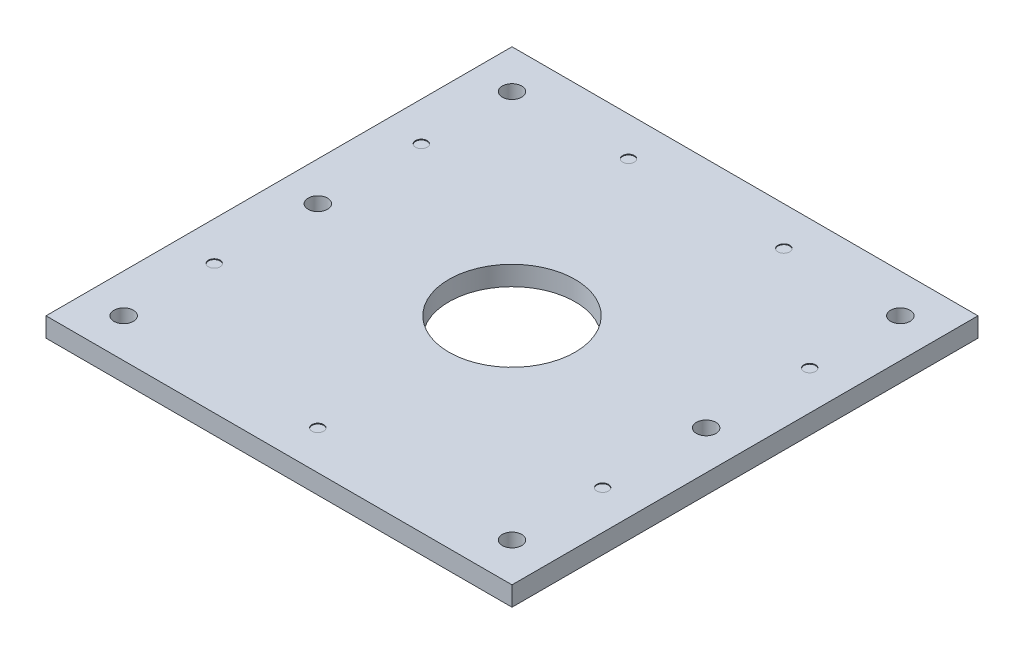
SolidWorks part; units mm, degrees
ref_plane "Front Plane" through (0, 0, 0) normal (0, 0, 1) x (1, 0, 0)
ref_plane "Top Plane" through (0, 0, 0) normal (0, 1, 0) x (1, 0, 0)
ref_plane "Right Plane" through (0, 0, 0) normal (1, 0, 0) x (0, 0, -1)
sketch "Sketch1" plane through (0, 0, 0) normal (0, 0, 1) x (1, 0, 0)
  line L7 (-76.2, -3.175) -> (76.2, -3.175)
  line L8 (-76.2, -3.175) -> (-76.2, 3.175)
  line L9 (-76.2, 3.175) -> (76.2, 3.175)
  line L10 (76.2, -3.175) -> (76.2, 3.175)
  line L11 (-76.2, -3.175) -> (76.2, 3.175) construction
  line L12 (-76.2, 3.175) -> (76.2, -3.175) construction
  point P4 (0, 0)
  point P14 (0, 0)
  dimension "Thickness" = 6.35
  dimension "Width" = 152.4
sketch "Sketch2" plane through (0, 0, 0) normal (0, 1, 0) x (0, 0, -1)
  line L0 (76.2, 76.2) -> (-76.2, 76.2) construction
  point P4 (0, 76.2)
  dimension "Length" = 152.4
sketch "Sketch3" plane through (0, 0, 0) normal (0, 0, 1) x (1, 0, 0)
  line L6 (-76.2, 3.175) -> (76.2, 3.175)
  line L7 (76.2, 3.175) -> (76.2, -3.175)
  line L8 (76.2, -3.175) -> (-76.2, -3.175)
  line L9 (-76.2, -3.175) -> (-76.2, 3.175)
extrude "Boss-Extrude1" add sketch "Sketch3" along normal mid plane 152.4
sketch "Sketch4" plane through (0, 3.175, 0) normal (0, 1, 0) x (1, 0, 0)
  line L0 (-76.2, -76.2) -> (-76.2, 76.2) construction
  line L1 (76.2, 76.2) -> (-76.2, 76.2) construction
  line L2 (76.2, -76.2) -> (76.2, 76.2) construction
  line L3 (76.2, -76.2) -> (-76.2, -76.2) construction
  circle A0 centre (-63.5, 63.5) radius 3.175
  circle A1 centre (63.5, 63.5) radius 3.175
  circle A2 centre (63.5, 0) radius 3.175
  circle A3 centre (63.5, -63.5) radius 3.175
  circle A4 centre (-63.5, -63.5) radius 3.175
  circle A5 centre (-63.5, 0) radius 3.175
  dimension "D4" = 6.35
  dimension "D1" = 12.7
  dimension "D2" = 12.7
  dimension "D3" = 12.7
  dimension "D5" = 12.7
extrude "Cut-Extrude1" cut sketch "Sketch4" against normal through all
sketch "Sketch5" plane through (0, 3.175, 0) normal (0, 1, 0) x (1, 0, 0)
  line L0 (76.2, 76.2) -> (-76.2, 76.2) construction
  line L1 (76.2, -76.2) -> (-76.2, -76.2) construction
  line L2 (-76.2, -76.2) -> (-76.2, 76.2) construction
  line L3 (76.2, -76.2) -> (76.2, 76.2) construction
  circle A0 centre (-25.4, 63.5) radius 1.905
  circle A1 centre (25.4, 63.5) radius 1.905
  circle A2 centre (63.5, 33.8667) radius 1.905
  circle A3 centre (63.5, -33.8667) radius 1.905
  circle A4 centre (0, -63.5) radius 1.905
  circle A5 centre (-63.5, -33.8667) radius 1.905
  circle A6 centre (-63.5, 33.8667) radius 1.905
  circle A9 centre (63.5, -63.5) radius 3.175 construction
  circle A10 centre (-63.5, 63.5) radius 3.175 construction
  circle A11 centre (63.5, -63.5) radius 3.175
  circle A12 centre (-63.5, 63.5) radius 3.175
  dimension "D1" = 3.81
  dimension "D2" = 42.3333
  dimension "D3" = 42.3333
  dimension "D4" = 50.8
  dimension "D5" = 50.8
extrude "Cut-Extrude2" cut sketch "Sketch5" against normal blind 0.254
sketch "Sketch6" plane through (0, 3.175, 0) normal (0, 1, 0) x (1, 0, 0)
  circle A0 centre (0, 0) radius 20.6375
  dimension "D1" = 41.275
extrude "Cut-Extrude3" cut sketch "Sketch6" against normal through all
equation "\"D1@Boss-Extrude1\" = \"Length@Sketch2\""
